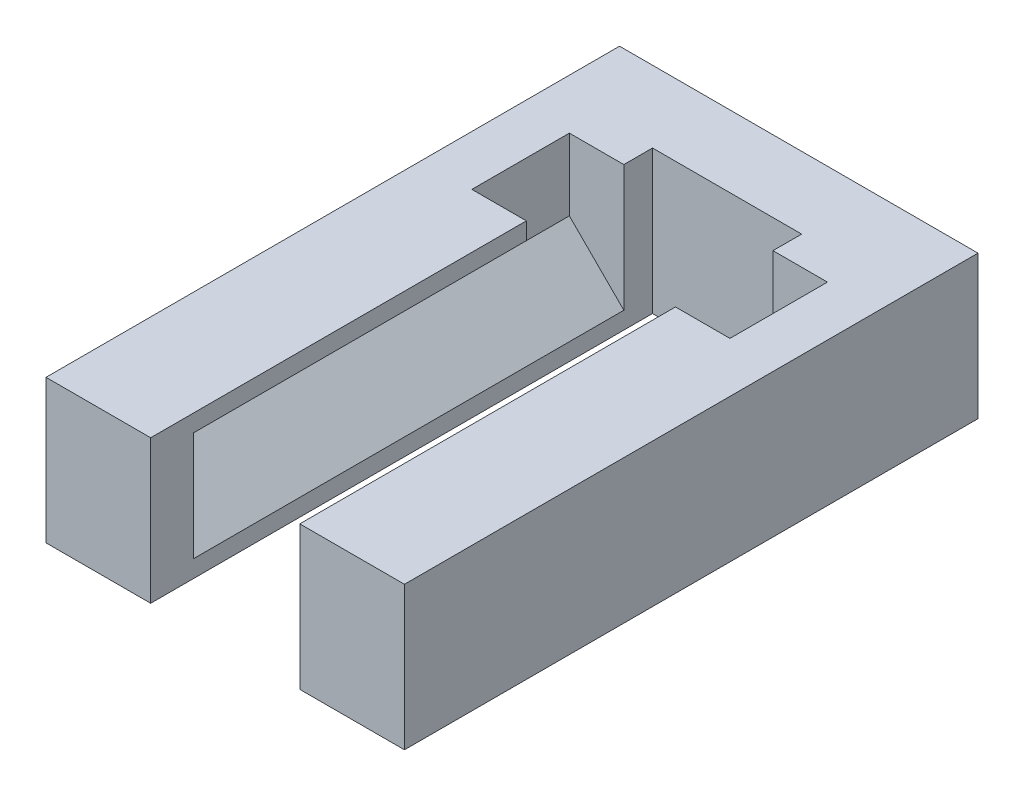
SolidWorks part; units mm, degrees
ref_plane "Front Plane" through (0, 0, 0) normal (0, 0, 1) x (1, 0, 0)
ref_plane "Top Plane" through (0, 0, 0) normal (0, 1, 0) x (1, 0, 0)
ref_plane "Right Plane" through (0, 0, 0) normal (1, 0, 0) x (0, 0, -1)
sketch "Sketch2" plane through (0, 0, 0) normal (0, 0, 1) x (1, 0, 0)
  line L1 (-12.5, 5) -> (12.5, 5)
  line L2 (-12.5, 5) -> (-12.5, -5)
  line L3 (-12.5, -5) -> (12.5, -5)
  line L4 (12.5, 5) -> (12.5, -5)
  point P4 (0, -5)
  point P5 (12.5, 0)
  dimension "D1" = 10
  dimension "D2" = 25
extrude "Boss-Extrude1" add sketch "Sketch2" along normal blind 40
sketch "Sketch3" plane through (0, 5, 0) normal (0, 1, 0) x (1, 0, 0)
  line L0 (12.5, -40) -> (-12.5, -40) construction
  line L1 (-5.2, -5) -> (5.2, -5)
  line L2 (-5.2, -5) -> (-5.2, -40)
  line L3 (-5.2, -40) -> (5.2, -40)
  line L4 (5.2, -5) -> (5.2, -40)
  point P7 (0, -5)
  dimension "D1" = 5
  dimension "D2" = 10.4
extrude "Cut-Extrude1" cut sketch "Sketch3" against normal through all
sketch "Sketch4" plane through (0, 5, 0) normal (0, 1, 0) x (1, 0, 0)
  line L0 (5.2, -5) -> (-5.2, -5) construction
  line L1 (-9, -7) -> (9, -7)
  line L2 (-9, -7) -> (-9, -13.8)
  line L3 (-9, -13.8) -> (9, -13.8)
  line L4 (9, -7) -> (9, -13.8)
  line L5 (5.2, -40) -> (5.2, -5) construction
  line L6 (-5.2, -5) -> (-5.2, -40) construction
  dimension "D1" = 2
  dimension "D2" = 3.8
  dimension "D3" = 3.8
  dimension "D4" = 6.8
extrude "Cut-Extrude2" cut sketch "Sketch4" against normal blind 5
sketch "Sketch5" plane through (0, 0, 7) normal (0, 0, 1) x (1, 0, 0)
  line L0 (5.2, 3.8) -> (9, 0)
  line L1 (9, 0) -> (5.2, -3.8)
  line L2 (5.2, -3.8) -> (5.2, 3.8)
  line L4 (9, 0) -> (9, 5) construction
  line L5 (5.2, -5) -> (5.2, 5) construction
  line L6 (0, -5.5) -> (0, 5.5) construction
  line L7 (-5.2, -3.8) -> (-5.2, 3.8)
  line L8 (-9, 0) -> (-5.2, -3.8)
  line L9 (-5.2, 3.8) -> (-9, 0)
  point P2 (5.0857, -3.8013)
  point P5 (0, 0)
  point P9 (0, 0)
  point P10 (5.2, 0)
  point P12 (5.2, -3.8)
  point P13 (5.2, 3.7147)
  dimension "D1" = 90
extrude "Cut-Extrude3" cut sketch "Sketch5" along normal blind 30
